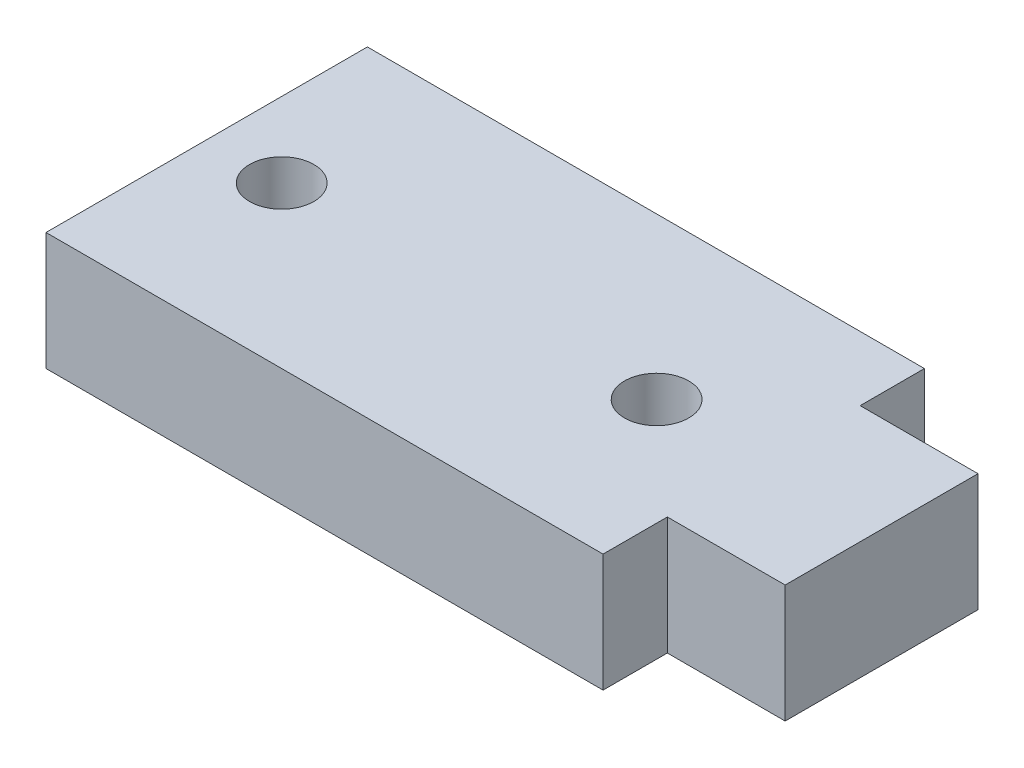
SolidWorks part; units mm, degrees
ref_plane "Alzado" through (0, 0, 0) normal (0, 0, 1) x (1, 0, 0)
ref_plane "Planta" through (0, 0, 0) normal (0, 1, 0) x (1, 0, 0)
ref_plane "Vista lateral" through (0, 0, 0) normal (1, 0, 0) x (0, 0, -1)
sketch "Croquis1" plane through (0, 0, 0) normal (0, 1, 0) x (1, 0, 0)
  line L0 (-70.3182, 2.2045) -> (-66.8182, 2.2045) construction
  line L1 (-70.3182, 9.7045) -> (-44.3182, 9.7045)
  line L2 (-70.3182, 9.7045) -> (-70.3182, -5.2955)
  line L3 (-70.3182, -5.2955) -> (-44.3182, -5.2955)
  line L4 (-38.8182, 6.7045) -> (-38.8182, -2.2955)
  line L5 (-66.8182, 2.2045) -> (-49.3182, 2.2045) construction
  line L7 (-44.3182, -5.2955) -> (-44.3182, -2.2955)
  line L8 (-44.3182, -2.2955) -> (-38.8182, -2.2955)
  line L9 (-44.3182, 9.7045) -> (-44.3182, 6.7045)
  line L10 (-44.3182, 6.7045) -> (-38.8182, 6.7045)
  circle A0 centre (-66.8182, 2.2045) radius 1.5
  circle A1 centre (-49.3182, 2.2045) radius 1.5
  dimension "D4" = 3
  dimension "D6" = 3
  dimension "D1" = 26
  dimension "D2" = 5.5
  dimension "D3" = 3.5
  dimension "D5" = 17.5
  dimension "D8" = 3
extrude "Saliente-Extruir1" add sketch "Croquis1" along normal blind 5.5
